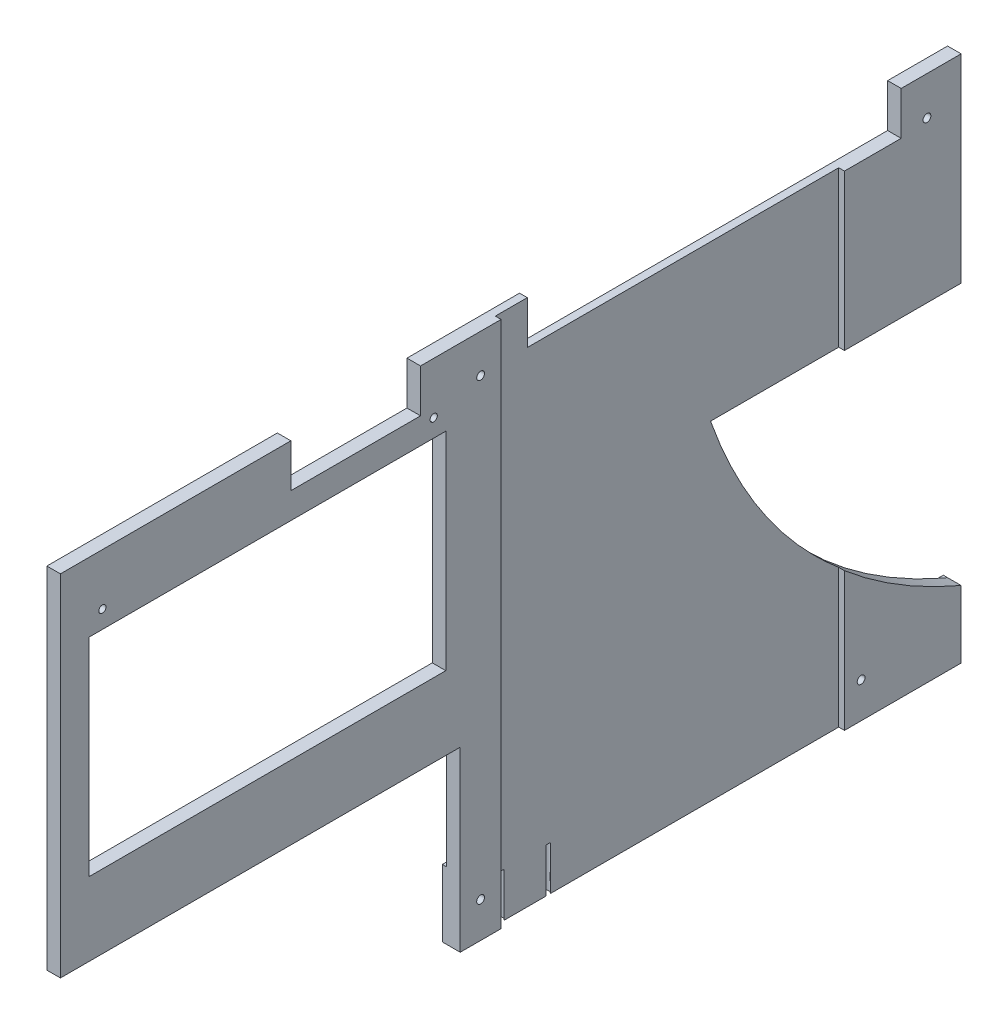
SolidWorks part; units mm, degrees
other "DetailItem1"
other "DetailItem2"
other "Markup1"
sketch "Sketch7" plane through (10, 0, 0) normal (1, 0, 0) x (0, 0, -1)
ref_plane "Front Plane" through (0, 0, 0) normal (0, 0, 1) x (1, 0, 0)
ref_plane "Top Plane" through (0, 0, 0) normal (0, 1, 0) x (1, 0, 0)
ref_plane "Right Plane" through (0, 0, 0) normal (1, 0, 0) x (0, 0, -1)
sketch "Sketch1" plane through (0, 0, 0) normal (1, 0, 0) x (0, 0, -1)
  line L1 (0, 0) -> (-312.66, 0)
  line L2 (0, 0) -> (0, 183.16)
  line L3 (0, 183.16) -> (-312.66, 183.16)
  line L4 (-312.66, 0) -> (-312.66, 183.16)
  dimension "D2" = 312.66
  dimension "D1" = 183.16
extrude "body" add sketch "Sketch1" along normal blind 4.7
sketch "itx_dims" plane through (4.7, 0, 0) normal (1, 0, 0) x (0, 0, -1)
  line L0 (-11.86, 169.81) -> (-11.86, 12.33) construction
  line L1 (-1.7, 5.98) -> (-171.88, 5.98)
  line L2 (-1.7, 5.98) -> (-1.7, 176.16)
  line L3 (-1.7, 176.16) -> (-171.88, 176.16)
  line L4 (-171.88, 5.98) -> (-171.88, 176.16)
  line L5 (-11.86, 12.33) -> (-34.72, 12.33) construction
  line L6 (-34.72, 12.33) -> (-166.8, 12.33) construction
  line L7 (-166.8, 12.33) -> (-166.8, 169.81) construction
  line L8 (-166.8, 169.81) -> (-11.86, 169.81) construction
  line L9 (-11.86, 169.81) -> (-1.7, 169.81) construction
  line L10 (-6.5301, 162.29) -> (-6.5301, 3.54) construction
  line L11 (-11.86, 169.81) -> (-11.86, 176.16) construction
  line L12 (0, 0) -> (0, 183.16) construction
  line L13 (-312.66, 0) -> (0, 0) construction
  line L15 (-1.7, 5.98) -> (-6.5301, 5.98) construction
  line L16 (-1.7, 5.98) -> (-1.7, 162.29) construction
  line L17 (-1.7, 162.29) -> (-6.5301, 162.29) construction
  dimension "D1" = 170.18
  dimension "D2" = 170.18
  dimension "D3" = 157.48
  dimension "D4" = 22.86
  dimension "D5" = 6.35
  dimension "D6" = 10.16
  dimension "D7" = 154.94
  dimension "D8" = 5.98
  dimension "D9" = 2.44
  dimension "D10" = 158.75
  dimension "D11" = 5.3299
  dimension "D12" = 4.8301
  dimension "D13" = 1.7
  dimension "D14" = 6.35
hole_wizard "#6-32 Tapped Hole1" positions "3DSketch2" profile "Sketch3" tap size "#6-32" standard "ANSI Inch" end condition through all
sketch3d "3DSketch2"
  point P20 (4.7, 169.81, 166.8)
  point P23 (4.7, 169.81, 11.86)
  point P26 (4.7, 12.33, 34.72)
  point P29 (4.7, 12.33, 166.8)
sketch "Sketch3" plane through (4.7, 169.81, 166.8) normal (0, 1, 0) x (0, 0, -1)
  line L0 (0, 0) -> (0, 4.7)
  line L1 (0, 4.7) -> (1.3525, 4.7)
  line L2 (1.3525, 4.7) -> (1.3525, 0)
  line L5 (1.3525, 0) -> (0, 0)
  line L11 (0, -6.35) -> (0, 107.95) construction
  dimension "Thru Tap Drill Dia." = 2.7051
  dimension "Thru Tap Drill Depth" = 4.7
cosmetic thread "Hole Thread1" parameters "D2"=3.5052
cosmetic thread "Hole Thread2" parameters "D2"=3.5052
cosmetic thread "Hole Thread3" parameters "D2"=3.5052
cosmetic thread "Hole Thread4" parameters "D2"=3.5052
sketch "Sketch8" plane through (4.7, 0, 0) normal (1, 0, 0) x (0, 0, -1)
  line L0 (0, 183.16) -> (-312.66, 183.16) construction
  line L1 (-148.5807, 183.16) -> (-20.81, 183.16)
  line L2 (-148.5807, 183.16) -> (-148.5807, 176.16)
  line L3 (-148.5807, 176.16) -> (-20.81, 176.16) construction
  line L4 (-20.81, 183.16) -> (-20.81, 176.16)
  line L5 (-148.5807, 176.16) -> (-148.5807, 168.16)
  line L6 (-148.5807, 168.16) -> (-20.81, 168.16)
  line L7 (-20.81, 168.16) -> (-20.81, 176.16)
  dimension "D1" = 7
  dimension "D2" = 8
extrude "riser-cable-cutout" cut sketch "Sketch8" against normal up to next
sketch "sfx_psu_footprint" plane through (4.7, 0, 0) normal (1, 0, 0) x (0, 0, -1)
  line L0 (-171.88, 5.98) -> (-171.88, 176.16) construction
  line L1 (-299.88, 158.16) -> (-174.88, 158.16)
  line L2 (-299.88, 158.16) -> (-299.88, 58.16)
  line L3 (-299.88, 58.16) -> (-174.88, 58.16)
  line L4 (-174.88, 158.16) -> (-174.88, 58.16)
  line L7 (-148.5807, 183.16) -> (-312.66, 183.16) construction
  dimension "D1" = 125
  dimension "D2" = 100
  dimension "D4" = 25
  dimension "D3" = 3
sketch "Sketch11" plane through (4.7, 0, 0) normal (1, 0, 0) x (0, 0, -1)
  line L0 (-148.5807, 183.16) -> (-312.66, 183.16) construction
  line L1 (-312.66, 0) -> (-173.88, 0)
  line L2 (-312.66, 0) -> (-312.66, 61.66)
  line L3 (-312.66, 61.66) -> (-173.88, 61.66)
  line L4 (-173.88, 0) -> (-173.88, 61.66)
  line L5 (-171.88, 5.98) -> (-171.88, 176.16) construction
  dimension "D1" = 121.5
  dimension "D2" = 2
extrude "expansion-cutout" cut sketch "Sketch11" against normal up to next
sketch "ssd_footprint" plane through (4.7, 0, 0) normal (1, 0, 0) x (0, 0, -1)
  line L1 (-292.7083, 155.2671) -> (-192.5083, 155.2671)
  line L2 (-292.7083, 155.2671) -> (-292.7083, 85.2671)
  line L3 (-292.7083, 85.2671) -> (-192.5083, 85.2671)
  line L4 (-192.5083, 155.2671) -> (-192.5083, 85.2671)
  dimension "D1" = 70
  dimension "D2" = 100.2
sketch "Sketch20" plane through (4.7, 0, 0) normal (1, 0, 0) x (0, 0, -1)
  line L1 (-232.66, 183.16) -> (-187.66, 183.16)
  line L2 (-232.66, 183.16) -> (-232.66, 168.16)
  line L3 (-232.66, 168.16) -> (-187.66, 168.16)
  line L4 (-187.66, 183.16) -> (-187.66, 168.16)
  line L5 (-312.66, 183.16) -> (-312.66, 61.66) construction
  line L6 (-148.5807, 183.16) -> (-312.66, 183.16) construction
  dimension "D1" = 15
  dimension "D2" = 45
  dimension "D3" = 80
extrude "psu-cable-cutout" cut sketch "Sketch20" against normal up to next
sketch "Sketch22" plane through (4.7, 0, 0) normal (1, 0, 0) x (0, 0, -1)
  line L1 (-178.88, 159.16) -> (-302.66, 159.16)
  line L2 (-178.88, 159.16) -> (-178.88, 87.16)
  line L3 (-178.88, 87.16) -> (-302.66, 87.16)
  line L4 (-302.66, 159.16) -> (-302.66, 87.16)
  line L6 (-299.88, 158.16) -> (-174.88, 158.16) construction
  line L7 (-312.66, 183.16) -> (-312.66, 61.66) construction
  line L8 (-173.88, 0) -> (-173.88, 61.66) construction
  dimension "D1" = 72
  dimension "D2" = 5
  dimension "D3" = 1
  dimension "D4" = 10
extrude "ssd-access-cutout" cut sketch "Sketch22" against normal up to next
hole_wizard "Tap Drill for M3x0.5 Tap1" positions "Sketch25" profile "Sketch26" hole size "M3x0.5" standard "ANSI Metric" end condition through all
sketch "Sketch25" plane through (4.7, 0, 0) normal (1, 0, 0) x (0, 0, -1)
  point P0 (-298.08, 165.31)
  point P3 (-183.08, 165.31)
sketch "Sketch26" plane through (4.7, 165.31, 298.08) normal (0, 1, 0) x (0, 0, -1)
  line L0 (0, 0) -> (0, 4.7)
  line L1 (0, 4.7) -> (1.25, 4.7)
  line L2 (1.25, 4.7) -> (1.25, 0)
  line L5 (1.25, 0) -> (0, 0)
  line L11 (0, -6.35) -> (0, 107.95) construction
  dimension "Thru Hole Dia." = 2.5
  dimension "Thru Hole Depth" = 4.7
sketch "Sketch27" plane through (4.7, 0, 0) normal (1, 0, 0) x (0, 0, -1)
  line L0 (0, 114.21) -> (-84.98, 114.21)
  line L2 (0, 0) -> (0, 183.16) construction
  line L3 (0, 114.21) -> (0, 23.33)
  line L5 (0, 183.16) -> (-20.81, 183.16) construction
  line L6 (-173.88, 0) -> (-173.88, 61.66) construction
  spline S0 degree 2 poles (-84.98, 114.21) (-62.1765, 49.8393) (0, 23.33) knots 0 0 0 1 1 1
  dimension "D1" = 68.95
  dimension "D2" = 88.9
  dimension "D3" = 23.33
extrude "hole-in-stock" cut sketch "Sketch27" against normal up to next
sketch "Sketch33" plane through (0, 0, 0) normal (-1, 0, 0) x (0, 0, 1)
  line L1 (0, 23.33) -> (173.88, 23.33)
  line L2 (0, 23.33) -> (0, 0)
  line L3 (0, 0) -> (173.88, 0)
  line L4 (173.88, 23.33) -> (173.88, 0)
extrude "Boss-Extrude1" add sketch "Sketch33" along normal blind 1.5
sketch "Sketch28" plane through (0, 0, 0) normal (0, 0, -1) x (-1, 0, 0)
  line L0 (-2.35, 183.16) -> (-2.35, 170.335)
  line L1 (-4.7, 183.16) -> (0, 183.16) construction
sketch "underside-centerline" plane through (0, 0, 0) normal (0, -1, 0) x (-1, 0, 0)
  line L0 (-1.6, 0) -> (-1.6, -173.88) construction
  line L4 (-4.7, 0) -> (1.5, 0) construction
hole_wizard "Tap Drill for #6-32 Tap1" positions "Sketch30" profile "Sketch31" hole size "#6-32" standard "ANSI Inch"
sketch "Sketch30" plane through (0, 0, 0) normal (0, -1, 0) x (-1, 0, 0)
  line L0 (-1.6, 0) -> (-1.6, -173.88) construction
  point P4 (-1.6, -141.3865)
  point P7 (-1.6, -157.4463)
sketch "Sketch31" plane through (1.6, 0, 157.4463) normal (1, 0, 0) x (0, 0, -1)
  line L0 (0, 0) -> (0, 16.0527)
  line L1 (0, 16.0527) -> (1.3525, 15.24)
  line L2 (1.3525, 15.24) -> (1.3525, 0)
  line L5 (1.3525, 0) -> (0, 0)
  line L10 (0, 16.0527) -> (-1.3526, 15.24) construction
  line L11 (0, -6.35) -> (0, 107.95) construction
  dimension "Hole Dia." = 2.7051
  dimension "Hole Depth" = 15.24
  dimension "Drill Angle" = 118
sketch "front-centerline" plane through (0, 0, 312.66) normal (0, 0, 1) x (1, 0, 0)
  line L0 (2.35, 61.66) -> (2.35, 183.16) construction
  line L1 (0, 61.66) -> (4.7, 61.66) construction
  line L2 (4.7, 183.16) -> (0, 183.16) construction
sketch "back-centerline" plane through (0, 0, 0) normal (0, 0, -1) x (-1, 0, 0)
  line L0 (-2.35, 0) -> (-2.35, 183.16) construction
  line L2 (-4.7, 183.16) -> (0, 183.16) construction
sketch "Sketch32" plane through (4.7, 0, 0) normal (1, 0, 0) x (0, 0, -1)
  line L0 (0, 0) -> (-173.88, 0) construction
  line L1 (-40.4975, 0) -> (-159.684, 0)
  line L2 (-40.4975, 0) -> (-40.4975, 183.16)
  line L3 (-40.4975, 183.16) -> (-159.684, 183.16)
  line L4 (-159.684, 0) -> (-159.684, 183.16)
  line L5 (-148.5807, 183.16) -> (-187.66, 183.16) construction
extrude "Cut-Extrude1" cut sketch "Sketch32" against normal blind 2
equation "\"mobo-floor-clearance\"= \"io-shield-overhang\" + \"io-shield-keepout\" + 1mm"
equation "\"D8@itx_dims\"=\"mobo-floor-clearance\""
equation "\"riser-clearance\"= 7mm"
equation "\"itx-side-length\"= 6.7in"
equation "\"D1@Sketch8\"=\"riser-clearance\""
equation "\"m3-screwhead-size\"= 6.75mm"
equation "\"modular-cable-clearance\"= 30mm"
equation "\"right-angle-c14-clearance\"= 23mm"
equation "\"sfx-length\"= 125mm"
equation "\"io-shield-overhang\"= 2.44mm"
equation "\"io-shield-keepout\"= 2.54mm"
equation "\"spine-thickness\"= 4.7mm"
equation "\"D1@body\"=\"spine-thickness\""
equation "\"spine-length\"= 315mm - 2 * \"steel-thickness\"'\"steel-thickness\""
equation "\"D2@Sketch1\"=\"spine-length\""
equation "\"spine-height\"= \"mobo-floor-clearance\" + \"itx-side-length\" + \"riser-clearance\""
equation "\"D1@Sketch1\"=\"spine-height\""
equation "\"D4@sfx_psu_footprint\"=\"right-angle-c14-clearance\"+2mm"
equation "\"right-angle-sata-clearance\"= 16.5mm"
equation "\"D2@Sketch8\"=15-\"riser-clearance\""
equation "\"steel-thickness\"= 1.17mm"
